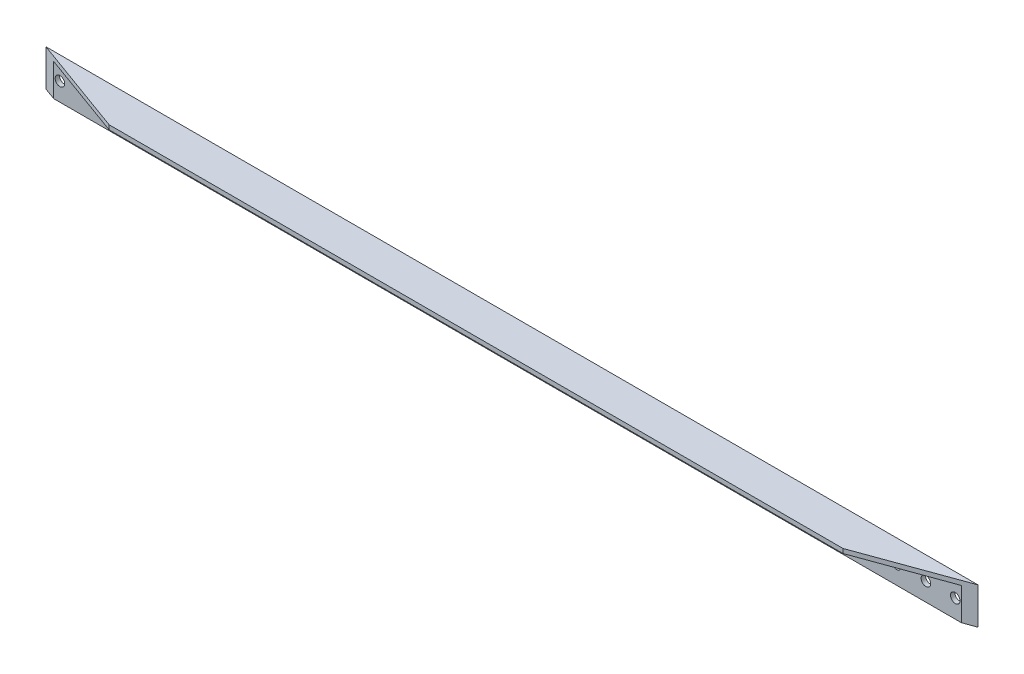
SolidWorks part; units mm, degrees
ref_plane "前视" through (0, 0, 0) normal (0, 0, 1) x (1, 0, 0)
ref_plane "上视" through (0, 0, 0) normal (0, 1, 0) x (1, 0, 0)
ref_plane "右视" through (0, 0, 0) normal (1, 0, 0) x (0, 0, -1)
sketch "草图1" plane through (0, 0, 0) normal (0, 0, 1) x (1, 0, 0)
  line L0 (-514.4277, 0) -> (1448.6337, 0) construction
  line L1 (-1270, 50) -> (1270, 50)
  line L2 (-1270, 50) -> (-1270, -50)
  line L3 (-1270, -50) -> (1270, -50)
  line L4 (1270, 50) -> (1270, -50)
  line L5 (0, 212.5086) -> (0, -250.4285) construction
  circle A0 centre (1220, 0) radius 13
  circle A1 centre (1140, 0) radius 13
  circle A2 centre (1060, 0) radius 13
  circle A3 centre (980, 0) radius 13
  circle A4 centre (580, 0) radius 13
  circle A5 centre (460, 0) radius 13
  circle A6 centre (380, 0) radius 13
  circle A7 centre (300, 0) radius 13
  circle A8 centre (180, 0) radius 13
  circle A9 centre (-180, 0) radius 13
  circle A10 centre (-300, 0) radius 13
  circle A11 centre (-380, 0) radius 13
  circle A12 centre (-460, 0) radius 13
  circle A13 centre (-580, 0) radius 13
  circle A14 centre (-980, 0) radius 13
  circle A15 centre (-1060, 0) radius 13
  circle A16 centre (-1140, 0) radius 13
  circle A17 centre (-1220, 0) radius 13
  dimension "D3" = 50
  dimension "D12" = 26
  dimension "D1" = 50
  dimension "D2" = 2540
  dimension "D4" = 80
  dimension "D5" = 80
  dimension "D6" = 80
  dimension "D7" = 400
  dimension "D8" = 120
  dimension "D9" = 80
  dimension "D10" = 80
  dimension "D11" = 120
extrude "基体-拉伸" add sketch "草图1" along normal blind 12
sketch "草图2" plane through (0, 0, 12) normal (0, 0, 1) x (1, 0, 0)
  line L1 (-1270, 50) -> (1270, 50)
  line L2 (-1270, 50) -> (-1270, 38)
  line L3 (-1270, 38) -> (1270, 38)
  line L4 (1270, 50) -> (1270, 38)
  dimension "D1" = 12
extrude "凸台-拉伸1" add sketch "草图2" along normal blind 86
sketch "草图4" plane through (0, 50, 0) normal (0, 1, 0) x (-1, 0, 0)
  line L0 (-1270, 0) -> (-1270, 98)
  line L3 (-1270, 98) -> (-1000, 98)
  line L4 (-1270, 98) -> (1270, 98) construction
  line L5 (-1270, 0) -> (-1000, 98)
  line L6 (0, 322.0836) -> (0, -403.7798) construction
  line L7 (1270, 0) -> (1000, 98)
  line L8 (1270, 98) -> (1000, 98)
  line L9 (1270, 0) -> (1270, 98)
  dimension "D1" = 270
extrude "切除-拉伸1" cut sketch "草图4" against normal through all
